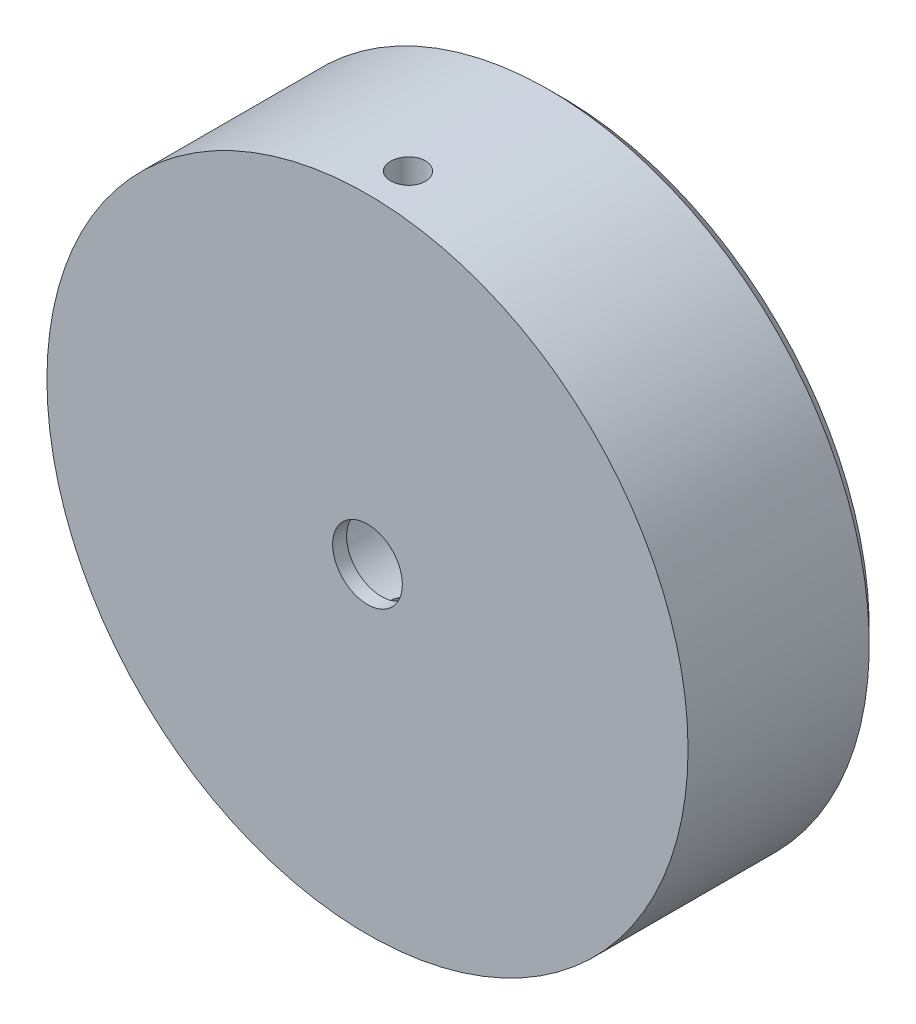
SolidWorks part; units mm, degrees
material "Liga 6061"
ref_plane "Plano frontal" through (0, 0, 0) normal (0, 0, 1) x (1, 0, 0)
ref_plane "Plano superior" through (0, 0, 0) normal (0, 1, 0) x (1, 0, 0)
ref_plane "Plano direito" through (0, 0, 0) normal (1, 0, 0) x (0, 0, -1)
sketch "Esboço1" plane through (0, 0, 0) normal (0, 0, 1) x (1, 0, 0)
  circle A0 centre (0, 0) radius 13.905
  circle A1 centre (0, 0) radius 23
extrude "Ressalto-extrusão1" add sketch "Esboço1" along normal blind 11
sketch "Esboço2" plane through (0, 0, 11) normal (0, 0, 1) x (1, 0, 0)
  circle A0 centre (0, 0) radius 23
extrude "Ressalto-extrusão2" add sketch "Esboço2" along normal blind 5
sketch "Esboço3" plane through (0, 0, 16) normal (0, 0, 1) x (1, 0, 0)
  circle A0 centre (0, 0) radius 2.5
extrude "Corte-extrusão1" cut sketch "Esboço3" against normal blind 18
sketch "Esboço4" plane through (0, 0, 11) normal (0, 0, -1) x (-1, 0, 0)
  circle A0 centre (0, 0) radius 4.5
extrude "Corte-extrusão2" cut sketch "Esboço4" against normal blind 4
sketch "Esboço5" plane through (0, 0, 16) normal (0, 0, 1) x (1, 0, 0)
  line L0 (0, 23) -> (0, -23) construction
  line L1 (-23, 0) -> (23, 0) construction
  line L2 (-2, 11.619) -> (-2, 7)
  line L4 (-11.619, 2) -> (-7, 2)
  line L5 (2, 11.619) -> (2, 7)
  line L6 (7, 2) -> (11.619, 2)
  line L8 (-23, 2) -> (23, 2) construction
  line L9 (2, -7) -> (2, -11.619)
  line L10 (-2, 23) -> (-2, -23) construction
  line L11 (7, -2) -> (11.619, -2)
  line L12 (2, 23) -> (2, -23) construction
  line L23 (-2, -7) -> (-2, -11.619)
  line L24 (-7, -2) -> (-11.619, -2)
  circle A0 centre (0, 0) radius 23 construction
  arc A1 (-2, 7) -> (-7, 2) centre (-7, 7) cw
  arc A22 (2, 7) -> (7, 2) centre (7, 7) ccw
  arc A23 (7, -2) -> (2, -7) centre (7, -7) ccw
  arc A27 (-3.25, 12.5872) -> (-12.5872, 3.25) centre (0, 0) ccw
  arc A28 (-3.25, -12.5872) -> (-2, -11.619) centre (-3, -11.619) ccw
  arc A30 (12.5872, 3.25) -> (3.25, 12.5872) centre (0, 0) ccw
  arc A31 (3.25, -12.5872) -> (12.5872, -3.25) centre (0, 0) ccw
  arc A32 (-12.5872, 3.25) -> (-11.619, 2) centre (-11.619, 3) ccw
  arc A33 (-3.25, 12.5872) -> (-2, 11.619) centre (-3, 11.619) cw
  arc A34 (3.25, 12.5872) -> (2, 11.619) centre (3, 11.619) ccw
  arc A35 (12.5872, 3.25) -> (11.619, 2) centre (11.619, 3) cw
  arc A36 (12.5872, -3.25) -> (11.619, -2) centre (11.619, -3) ccw
  arc A37 (3.25, -12.5872) -> (2, -11.619) centre (3, -11.619) cw
  arc A40 (-7, -2) -> (-2, -7) centre (-7, -7) cw
  arc A41 (-12.5872, -3.25) -> (-11.619, -2) centre (-11.619, -3) cw
  arc A42 (-3.25, -12.5872) -> (-12.5872, -3.25) centre (0, 0) cw
  point P9 (-20, -2)
  point P10 (20, -2)
  point P37 (2, -12.8452)
  point P41 (-2, 17.8885)
  point P44 (2, 17.8885)
  point P47 (17.8885, 2)
  point P50 (17.8885, -2)
  point P53 (2, -17.8885)
  dimension "D5" = 1
  dimension "D3" = 5
  dimension "D1" = 2
  dimension "D2" = 2
sketch "Esboço6" plane through (0, 0, 0) normal (0, 0, -1) x (-1, 0, 0)
  circle A0 centre (0, 0) radius 24.343
extrude "Corte-extrusão4" cut sketch "Esboço6" against normal blind 2
chamfer "Chanfro1" distance 1 angle 45 1 edges at (-23, 0, 2)
sketch "Esboço7" plane through (0, 0, 0) normal (0, 1, 0) x (1, 0, 0)
  line L0 (-4.5005, -10.998) -> (4.4672, -10.998) construction
  circle A0 centre (0, -13.098) radius 1.25
  dimension "D1" = 2.1
extrude "Corte-extrusão5" cut sketch "Esboço7" against normal blind 31 and the other way blind 30
